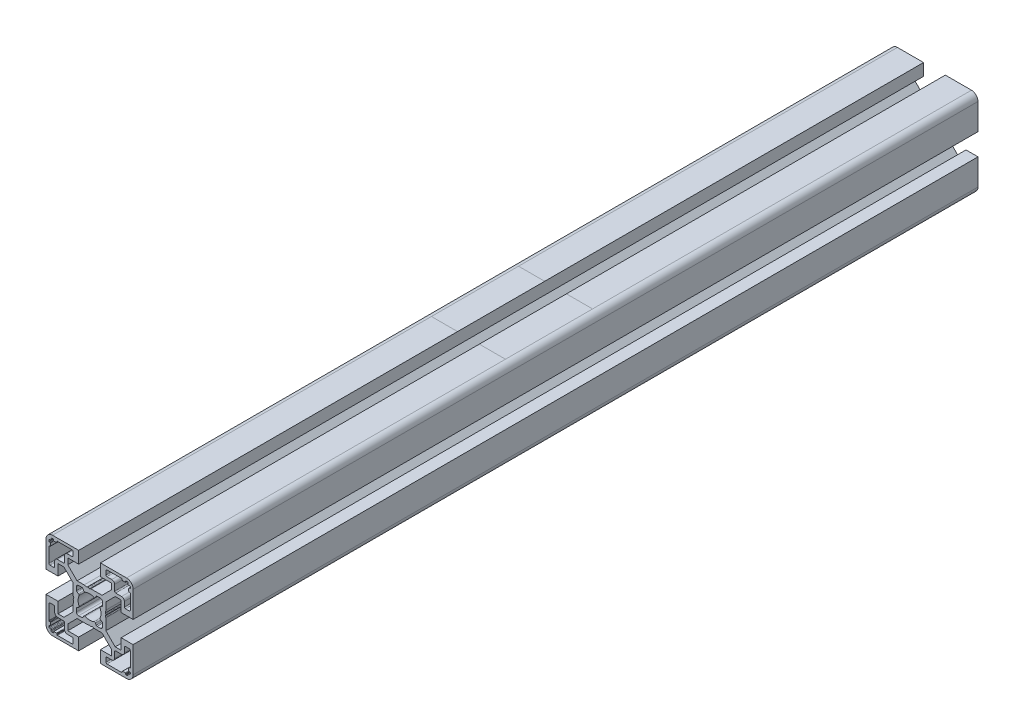
SolidWorks part; units mm, degrees
material "6063-T5"
ref_plane "Front Plane" through (0, 0, 0) normal (0, 0, 1) x (1, 0, 0)
ref_plane "Top Plane" through (0, 0, 0) normal (0, 1, 0) x (1, 0, 0)
ref_plane "Right Plane" through (0, 0, 0) normal (1, 0, 0) x (0, 0, -1)
ref_plane "Plan1" through (0, 0, 50) normal (0, 0, 1) x (1, 0, 0)
sketch "Esquisse1" plane through (0, 0, 50) normal (0, 0, 1) x (1, 0, 0)
  line L0 (-11.2645, -4.6769) -> (-11.2645, 2.1231)
  line L1 (-10.7645, 2.6231) -> (-9.0645, 2.6231)
  line L2 (-8.5645, 2.1231) -> (-8.5645, -0.0769)
  line L3 (-7.2645, -1.3769) -> (-4.5645, -1.3769)
  line L4 (-4.0645, -1.8769) -> (-4.0645, -4.5769)
  line L5 (-2.7645, -5.8769) -> (-0.5645, -5.8769)
  line L6 (-0.0645, -6.3769) -> (-0.0645, -8.0769)
  line L7 (-0.5645, -8.5769) -> (-7.3645, -8.5769)
  line L8 (-7.5645, -8.3769) -> (-7.5645, -8.0769)
  line L9 (-7.7645, -7.8769) -> (-8.9645, -7.8769)
  line L10 (-9.1645, -8.0769) -> (-9.1645, -8.3769)
  line L11 (-9.3645, -8.5769) -> (-9.8645, -8.5769)
  line L12 (-10.1645, -8.2769) -> (-10.1645, -7.7769)
  line L13 (-10.4645, -7.4769) -> (-10.9645, -7.4769)
  line L14 (-11.2645, -7.1769) -> (-11.2645, -6.6769)
  line L15 (-11.0645, -6.4769) -> (-10.7645, -6.4769)
  line L16 (-10.5645, -6.2769) -> (-10.5645, -5.0769)
  line L17 (-10.7645, -4.8769) -> (-11.0645, -4.8769)
  line L18 (14.9355, -8.0769) -> (14.9355, -6.3769)
  line L19 (15.4355, -5.8769) -> (17.6355, -5.8769)
  line L20 (18.9355, -4.5769) -> (18.9355, -1.8769)
  line L21 (19.4355, -1.3769) -> (22.1355, -1.3769)
  line L22 (23.4355, -0.0769) -> (23.4355, 2.1231)
  line L23 (23.9355, 2.6231) -> (25.6355, 2.6231)
  line L24 (26.1355, 2.1231) -> (26.1355, -4.6769)
  line L25 (25.9355, -4.8769) -> (25.6355, -4.8769)
  line L26 (25.4355, -5.0769) -> (25.4355, -6.2769)
  line L27 (25.6355, -6.4769) -> (25.9355, -6.4769)
  line L28 (26.1355, -6.6769) -> (26.1355, -7.1769)
  line L29 (25.8355, -7.4769) -> (25.3355, -7.4769)
  line L30 (25.0355, -7.7769) -> (25.0355, -8.2769)
  line L31 (24.7355, -8.5769) -> (24.2355, -8.5769)
  line L32 (24.0355, -8.3769) -> (24.0355, -8.0769)
  line L33 (23.8355, -7.8769) -> (22.6355, -7.8769)
  line L34 (22.4355, -8.0769) -> (22.4355, -8.3769)
  line L35 (22.2355, -8.5769) -> (15.4355, -8.5769)
  line L36 (-12.5645, 27.1231) -> (-12.5645, 15.1231)
  line L37 (-12.5645, 15.1231) -> (-7.0645, 15.1231)
  line L38 (-7.0645, 15.1231) -> (-7.0645, 20.1231)
  line L39 (-7.0645, 20.1231) -> (-4.3322, 20.1231)
  line L40 (-4.3322, 20.1231) -> (-0.0645, 15.8553)
  line L41 (-0.0645, 15.8553) -> (-0.0645, 10.7767)
  line L42 (0.0025, 10.5267) -> (0.2355, 10.1231)
  line L43 (0.2355, 10.1231) -> (0.0025, 9.7195)
  line L44 (0.0025, 9.2195) -> (0.1846, 8.9042)
  line L45 (0.1846, 8.9042) -> (-0.0645, 7.6231)
  line L46 (-0.0645, 7.6231) -> (-0.0645, 4.3908)
  line L47 (-0.0645, 4.3908) -> (-4.3322, 0.1231)
  line L48 (-4.3322, 0.1231) -> (-7.0645, 0.1231)
  line L49 (-7.0645, 0.1231) -> (-7.0645, 5.1231)
  line L50 (-7.0645, 5.1231) -> (-12.5645, 5.1231)
  line L51 (-12.5645, 5.1231) -> (-12.5645, -6.8769)
  line L52 (-9.5645, -9.8769) -> (2.4355, -9.8769)
  line L53 (2.4355, -9.8769) -> (2.4355, -4.3769)
  line L54 (2.4355, -4.3769) -> (-2.5645, -4.3769)
  line L55 (-2.5645, -4.3769) -> (-2.5645, -1.6447)
  line L56 (-2.5645, -1.6447) -> (1.7033, 2.6231)
  line L57 (1.7033, 2.6231) -> (6.7819, 2.6231)
  line L58 (7.0319, 2.6901) -> (7.4355, 2.9231)
  line L59 (7.4355, 2.9231) -> (7.8391, 2.6901)
  line L60 (8.3391, 2.6901) -> (8.6544, 2.8721)
  line L61 (8.6544, 2.8721) -> (9.9355, 2.6231)
  line L62 (9.9355, 2.6231) -> (13.1678, 2.6231)
  line L63 (13.1678, 2.6231) -> (17.4355, -1.6447)
  line L64 (17.4355, -1.6447) -> (17.4355, -4.3769)
  line L65 (17.4355, -4.3769) -> (12.4355, -4.3769)
  line L66 (12.4355, -4.3769) -> (12.4355, -9.8769)
  line L67 (12.4355, -9.8769) -> (24.4355, -9.8769)
  line L68 (27.4355, -6.8769) -> (27.4355, 5.1231)
  line L69 (27.4355, 5.1231) -> (21.9355, 5.1231)
  line L70 (21.9355, 5.1231) -> (21.9355, 0.1231)
  line L71 (21.9355, 0.1231) -> (19.2033, 0.1231)
  line L72 (19.2033, 0.1231) -> (14.9355, 4.3908)
  line L73 (14.9355, 4.3908) -> (14.9355, 9.4695)
  line L74 (14.8686, 9.7195) -> (14.6355, 10.1231)
  line L75 (14.6355, 10.1231) -> (14.8686, 10.5267)
  line L76 (14.8686, 11.0267) -> (14.6865, 11.342)
  line L77 (14.6865, 11.342) -> (14.9355, 12.6231)
  line L78 (14.9355, 12.6231) -> (14.9355, 15.8553)
  line L79 (14.9355, 15.8553) -> (19.2033, 20.1231)
  line L80 (19.2033, 20.1231) -> (21.9355, 20.1231)
  line L81 (21.9355, 20.1231) -> (21.9355, 15.1231)
  line L82 (21.9355, 15.1231) -> (27.4355, 15.1231)
  line L83 (27.4355, 15.1231) -> (27.4355, 27.1231)
  line L84 (24.4355, 30.1231) -> (12.4355, 30.1231)
  line L85 (12.4355, 30.1231) -> (12.4355, 24.6231)
  line L86 (12.4355, 24.6231) -> (17.4355, 24.6231)
  line L87 (17.4355, 24.6231) -> (17.4355, 21.8908)
  line L88 (17.4355, 21.8908) -> (13.1678, 17.6231)
  line L89 (13.1678, 17.6231) -> (8.0891, 17.6231)
  line L90 (7.8391, 17.5561) -> (7.4355, 17.3231)
  line L91 (7.4355, 17.3231) -> (7.0319, 17.5561)
  line L92 (6.5319, 17.5561) -> (6.2167, 17.3741)
  line L93 (6.2167, 17.3741) -> (4.9355, 17.6231)
  line L94 (4.9355, 17.6231) -> (1.7033, 17.6231)
  line L95 (1.7033, 17.6231) -> (-2.5645, 21.8908)
  line L96 (-2.5645, 21.8908) -> (-2.5645, 24.6231)
  line L97 (-2.5645, 24.6231) -> (2.4355, 24.6231)
  line L98 (2.4355, 24.6231) -> (2.4355, 30.1231)
  line L99 (2.4355, 30.1231) -> (-9.5645, 30.1231)
  line L100 (14.9355, 26.6231) -> (14.9355, 28.3231)
  line L101 (15.4355, 28.8231) -> (22.2355, 28.8231)
  line L102 (22.4355, 28.6231) -> (22.4355, 28.3231)
  line L103 (22.6355, 28.1231) -> (23.8355, 28.1231)
  line L104 (24.0355, 28.3231) -> (24.0355, 28.6231)
  line L105 (24.2355, 28.8231) -> (24.7355, 28.8231)
  line L106 (25.0355, 28.5231) -> (25.0355, 28.0231)
  line L107 (25.3355, 27.7231) -> (25.8355, 27.7231)
  line L108 (26.1355, 27.4231) -> (26.1355, 26.9231)
  line L109 (25.9355, 26.7231) -> (25.6355, 26.7231)
  line L110 (25.4355, 26.5231) -> (25.4355, 25.3231)
  line L111 (25.6355, 25.1231) -> (25.9355, 25.1231)
  line L112 (26.1355, 24.9231) -> (26.1355, 18.1231)
  line L113 (25.6355, 17.6231) -> (23.9355, 17.6231)
  line L114 (23.4355, 18.1231) -> (23.4355, 20.3231)
  line L115 (22.1355, 21.6231) -> (19.4355, 21.6231)
  line L116 (18.9355, 22.1231) -> (18.9355, 24.8231)
  line L117 (17.6355, 26.1231) -> (15.4355, 26.1231)
  line L118 (-11.2645, 18.1231) -> (-11.2645, 24.9231)
  line L119 (-11.0645, 25.1231) -> (-10.7645, 25.1231)
  line L120 (-10.5645, 25.3231) -> (-10.5645, 26.5231)
  line L121 (-10.7645, 26.7231) -> (-11.0645, 26.7231)
  line L122 (-11.2645, 26.9231) -> (-11.2645, 27.4231)
  line L123 (-10.9645, 27.7231) -> (-10.4645, 27.7231)
  line L124 (-10.1645, 28.0231) -> (-10.1645, 28.5231)
  line L125 (-9.8645, 28.8231) -> (-9.3645, 28.8231)
  line L126 (-9.1645, 28.6231) -> (-9.1645, 28.3231)
  line L127 (-8.9645, 28.1231) -> (-7.7645, 28.1231)
  line L128 (-7.5645, 28.3231) -> (-7.5645, 28.6231)
  line L129 (-7.3645, 28.8231) -> (-0.5645, 28.8231)
  line L130 (-0.0645, 28.3231) -> (-0.0645, 26.6231)
  line L131 (-0.5645, 26.1231) -> (-2.7645, 26.1231)
  line L132 (-4.0645, 24.8231) -> (-4.0645, 22.1231)
  line L133 (-4.5645, 21.6231) -> (-7.2645, 21.6231)
  line L134 (-8.5645, 20.3231) -> (-8.5645, 18.1231)
  line L135 (-9.0645, 17.6231) -> (-10.7645, 17.6231)
  line L136 (10.9262, 16.1231) -> (12.4355, 16.1231)
  line L137 (13.4355, 15.1231) -> (13.4355, 13.6138)
  line L138 (13.1703, 13.1723) -> (12.4933, 12.8123)
  line L139 (12.4933, 7.4338) -> (13.1703, 7.0739)
  line L140 (13.4355, 6.6324) -> (13.4355, 5.1231)
  line L141 (12.4355, 4.1231) -> (10.9262, 4.1231)
  line L142 (10.4848, 4.3883) -> (10.1248, 5.0654)
  line L143 (4.7463, 5.0654) -> (4.3863, 4.3883)
  line L144 (3.9449, 4.1231) -> (2.4355, 4.1231)
  line L145 (1.4355, 5.1231) -> (1.4355, 6.6324)
  line L146 (1.7008, 7.0739) -> (2.3778, 7.4338)
  line L147 (2.3778, 12.8123) -> (1.7008, 13.1723)
  line L148 (1.4355, 13.6138) -> (1.4355, 15.1231)
  line L149 (2.4355, 16.1231) -> (3.9449, 16.1231)
  line L150 (4.3863, 15.8578) -> (4.7463, 15.1808)
  line L151 (10.1248, 15.1808) -> (10.4848, 15.8578)
  arc A0 (-11.2645, 2.1231) -> (-10.7645, 2.6231) centre (-10.7645, 2.1231) cw
  arc A1 (-9.0645, 2.6231) -> (-8.5645, 2.1231) centre (-9.0645, 2.1231) cw
  arc A2 (-8.5645, -0.0769) -> (-7.2645, -1.3769) centre (-7.2645, -0.0769) ccw
  arc A3 (-4.5645, -1.3769) -> (-4.0645, -1.8769) centre (-4.5645, -1.8769) cw
  arc A4 (-4.0645, -4.5769) -> (-2.7645, -5.8769) centre (-2.7645, -4.5769) ccw
  arc A5 (-0.5645, -5.8769) -> (-0.0645, -6.3769) centre (-0.5645, -6.3769) cw
  arc A6 (-0.0645, -8.0769) -> (-0.5645, -8.5769) centre (-0.5645, -8.0769) cw
  arc A7 (-7.3645, -8.5769) -> (-7.5645, -8.3769) centre (-7.3645, -8.3769) cw
  arc A8 (-7.5645, -8.0769) -> (-7.7645, -7.8769) centre (-7.7645, -8.0769) ccw
  arc A9 (-8.9645, -7.8769) -> (-9.1645, -8.0769) centre (-8.9645, -8.0769) ccw
  arc A10 (-9.1645, -8.3769) -> (-9.3645, -8.5769) centre (-9.3645, -8.3769) cw
  arc A11 (-9.8645, -8.5769) -> (-10.1645, -8.2769) centre (-9.8645, -8.2769) cw
  arc A12 (-10.1645, -7.7769) -> (-10.4645, -7.4769) centre (-10.4645, -7.7769) ccw
  arc A13 (-10.9645, -7.4769) -> (-11.2645, -7.1769) centre (-10.9645, -7.1769) cw
  arc A14 (-11.2645, -6.6769) -> (-11.0645, -6.4769) centre (-11.0645, -6.6769) cw
  arc A15 (-10.7645, -6.4769) -> (-10.5645, -6.2769) centre (-10.7645, -6.2769) ccw
  arc A16 (-10.5645, -5.0769) -> (-10.7645, -4.8769) centre (-10.7645, -5.0769) ccw
  arc A17 (-11.0645, -4.8769) -> (-11.2645, -4.6769) centre (-11.0645, -4.6769) cw
  arc A18 (14.9355, -6.3769) -> (15.4355, -5.8769) centre (15.4355, -6.3769) cw
  arc A19 (17.6355, -5.8769) -> (18.9355, -4.5769) centre (17.6355, -4.5769) ccw
  arc A20 (18.9355, -1.8769) -> (19.4355, -1.3769) centre (19.4355, -1.8769) cw
  arc A21 (22.1355, -1.3769) -> (23.4355, -0.0769) centre (22.1355, -0.0769) ccw
  arc A22 (23.4355, 2.1231) -> (23.9355, 2.6231) centre (23.9355, 2.1231) cw
  arc A23 (25.6355, 2.6231) -> (26.1355, 2.1231) centre (25.6355, 2.1231) cw
  arc A24 (26.1355, -4.6769) -> (25.9355, -4.8769) centre (25.9355, -4.6769) cw
  arc A25 (25.6355, -4.8769) -> (25.4355, -5.0769) centre (25.6355, -5.0769) ccw
  arc A26 (25.4355, -6.2769) -> (25.6355, -6.4769) centre (25.6355, -6.2769) ccw
  arc A27 (25.9355, -6.4769) -> (26.1355, -6.6769) centre (25.9355, -6.6769) cw
  arc A28 (26.1355, -7.1769) -> (25.8355, -7.4769) centre (25.8355, -7.1769) cw
  arc A29 (25.3355, -7.4769) -> (25.0355, -7.7769) centre (25.3355, -7.7769) ccw
  arc A30 (25.0355, -8.2769) -> (24.7355, -8.5769) centre (24.7355, -8.2769) cw
  arc A31 (24.2355, -8.5769) -> (24.0355, -8.3769) centre (24.2355, -8.3769) cw
  arc A32 (24.0355, -8.0769) -> (23.8355, -7.8769) centre (23.8355, -8.0769) ccw
  arc A33 (22.6355, -7.8769) -> (22.4355, -8.0769) centre (22.6355, -8.0769) ccw
  arc A34 (22.4355, -8.3769) -> (22.2355, -8.5769) centre (22.2355, -8.3769) cw
  arc A35 (15.4355, -8.5769) -> (14.9355, -8.0769) centre (15.4355, -8.0769) cw
  arc A36 (-9.5645, 30.1231) -> (-12.5645, 27.1231) centre (-9.5645, 27.1231) ccw
  arc A37 (-0.0645, 10.7767) -> (0.0025, 10.5267) centre (0.4355, 10.7767) ccw
  arc A38 (0.0025, 9.7195) -> (0.0025, 9.2195) centre (0.4355, 9.4695) ccw
  arc A39 (-12.5645, -6.8769) -> (-9.5645, -9.8769) centre (-9.5645, -6.8769) ccw
  arc A40 (6.7819, 2.6231) -> (7.0319, 2.6901) centre (6.7819, 3.1231) ccw
  arc A41 (7.8391, 2.6901) -> (8.3391, 2.6901) centre (8.0891, 3.1231) ccw
  arc A42 (24.4355, -9.8769) -> (27.4355, -6.8769) centre (24.4355, -6.8769) ccw
  arc A43 (14.9355, 9.4695) -> (14.8686, 9.7195) centre (14.4355, 9.4695) ccw
  arc A44 (14.8686, 10.5267) -> (14.8686, 11.0267) centre (14.4355, 10.7767) ccw
  arc A45 (27.4355, 27.1231) -> (24.4355, 30.1231) centre (24.4355, 27.1231) ccw
  arc A46 (8.0891, 17.6231) -> (7.8391, 17.5561) centre (8.0891, 17.1231) ccw
  arc A47 (7.0319, 17.5561) -> (6.5319, 17.5561) centre (6.7819, 17.1231) ccw
  arc A48 (14.9355, 28.3231) -> (15.4355, 28.8231) centre (15.4355, 28.3231) cw
  arc A49 (22.2355, 28.8231) -> (22.4355, 28.6231) centre (22.2355, 28.6231) cw
  arc A50 (22.4355, 28.3231) -> (22.6355, 28.1231) centre (22.6355, 28.3231) ccw
  arc A51 (23.8355, 28.1231) -> (24.0355, 28.3231) centre (23.8355, 28.3231) ccw
  arc A52 (24.0355, 28.6231) -> (24.2355, 28.8231) centre (24.2355, 28.6231) cw
  arc A53 (24.7355, 28.8231) -> (25.0355, 28.5231) centre (24.7355, 28.5231) cw
  arc A54 (25.0355, 28.0231) -> (25.3355, 27.7231) centre (25.3355, 28.0231) ccw
  arc A55 (25.8355, 27.7231) -> (26.1355, 27.4231) centre (25.8355, 27.4231) cw
  arc A56 (26.1355, 26.9231) -> (25.9355, 26.7231) centre (25.9355, 26.9231) cw
  arc A57 (25.6355, 26.7231) -> (25.4355, 26.5231) centre (25.6355, 26.5231) ccw
  arc A58 (25.4355, 25.3231) -> (25.6355, 25.1231) centre (25.6355, 25.3231) ccw
  arc A59 (25.9355, 25.1231) -> (26.1355, 24.9231) centre (25.9355, 24.9231) cw
  arc A60 (26.1355, 18.1231) -> (25.6355, 17.6231) centre (25.6355, 18.1231) cw
  arc A61 (23.9355, 17.6231) -> (23.4355, 18.1231) centre (23.9355, 18.1231) cw
  arc A62 (23.4355, 20.3231) -> (22.1355, 21.6231) centre (22.1355, 20.3231) ccw
  arc A63 (19.4355, 21.6231) -> (18.9355, 22.1231) centre (19.4355, 22.1231) cw
  arc A64 (18.9355, 24.8231) -> (17.6355, 26.1231) centre (17.6355, 24.8231) ccw
  arc A65 (15.4355, 26.1231) -> (14.9355, 26.6231) centre (15.4355, 26.6231) cw
  arc A66 (-11.2645, 24.9231) -> (-11.0645, 25.1231) centre (-11.0645, 24.9231) cw
  arc A67 (-10.7645, 25.1231) -> (-10.5645, 25.3231) centre (-10.7645, 25.3231) ccw
  arc A68 (-10.5645, 26.5231) -> (-10.7645, 26.7231) centre (-10.7645, 26.5231) ccw
  arc A69 (-11.0645, 26.7231) -> (-11.2645, 26.9231) centre (-11.0645, 26.9231) cw
  arc A70 (-11.2645, 27.4231) -> (-10.9645, 27.7231) centre (-10.9645, 27.4231) cw
  arc A71 (-10.4645, 27.7231) -> (-10.1645, 28.0231) centre (-10.4645, 28.0231) ccw
  arc A72 (-10.1645, 28.5231) -> (-9.8645, 28.8231) centre (-9.8645, 28.5231) cw
  arc A73 (-9.3645, 28.8231) -> (-9.1645, 28.6231) centre (-9.3645, 28.6231) cw
  arc A74 (-9.1645, 28.3231) -> (-8.9645, 28.1231) centre (-8.9645, 28.3231) ccw
  arc A75 (-7.7645, 28.1231) -> (-7.5645, 28.3231) centre (-7.7645, 28.3231) ccw
  arc A76 (-7.5645, 28.6231) -> (-7.3645, 28.8231) centre (-7.3645, 28.6231) cw
  arc A77 (-0.5645, 28.8231) -> (-0.0645, 28.3231) centre (-0.5645, 28.3231) cw
  arc A78 (-0.0645, 26.6231) -> (-0.5645, 26.1231) centre (-0.5645, 26.6231) cw
  arc A79 (-2.7645, 26.1231) -> (-4.0645, 24.8231) centre (-2.7645, 24.8231) ccw
  arc A80 (-4.0645, 22.1231) -> (-4.5645, 21.6231) centre (-4.5645, 22.1231) cw
  arc A81 (-7.2645, 21.6231) -> (-8.5645, 20.3231) centre (-7.2645, 20.3231) ccw
  arc A82 (-8.5645, 18.1231) -> (-9.0645, 17.6231) centre (-9.0645, 18.1231) cw
  arc A83 (-10.7645, 17.6231) -> (-11.2645, 18.1231) centre (-10.7645, 18.1231) cw
  arc A84 (12.4355, 16.1231) -> (13.4355, 15.1231) centre (12.4355, 15.1231) cw
  arc A85 (13.4355, 13.6138) -> (13.1703, 13.1723) centre (12.9355, 13.6138) cw
  arc A86 (12.4933, 12.8123) -> (12.2678, 12.1754) centre (12.728, 12.3708) ccw
  arc A87 (12.2678, 12.1754) -> (12.2678, 8.0708) centre (7.4355, 10.1231) cw
  arc A88 (12.2678, 8.0708) -> (12.4933, 7.4338) centre (12.728, 7.8753) ccw
  arc A89 (13.1703, 7.0739) -> (13.4355, 6.6324) centre (12.9355, 6.6324) cw
  arc A90 (13.4355, 5.1231) -> (12.4355, 4.1231) centre (12.4355, 5.1231) cw
  arc A91 (10.9262, 4.1231) -> (10.4848, 4.3883) centre (10.9262, 4.6231) cw
  arc A92 (10.1248, 5.0654) -> (9.4878, 5.2908) centre (9.6833, 4.8306) ccw
  arc A93 (9.4878, 5.2908) -> (5.3832, 5.2908) centre (7.4355, 10.1231) cw
  arc A94 (5.3832, 5.2908) -> (4.7463, 5.0654) centre (5.1878, 4.8306) ccw
  arc A95 (4.3863, 4.3883) -> (3.9449, 4.1231) centre (3.9449, 4.6231) cw
  arc A96 (2.4355, 4.1231) -> (1.4355, 5.1231) centre (2.4355, 5.1231) cw
  arc A97 (1.4355, 6.6324) -> (1.7008, 7.0739) centre (1.9355, 6.6324) cw
  arc A98 (2.3778, 7.4338) -> (2.6033, 8.0708) centre (2.1431, 7.8753) ccw
  arc A99 (2.6033, 8.0708) -> (2.6033, 12.1754) centre (7.4355, 10.1231) cw
  arc A100 (2.6033, 12.1754) -> (2.3778, 12.8123) centre (2.1431, 12.3708) ccw
  arc A101 (1.7008, 13.1723) -> (1.4355, 13.6138) centre (1.9355, 13.6138) cw
  arc A102 (1.4355, 15.1231) -> (2.4355, 16.1231) centre (2.4355, 15.1231) cw
  arc A103 (3.9449, 16.1231) -> (4.3863, 15.8578) centre (3.9449, 15.6231) cw
  arc A104 (4.7463, 15.1808) -> (5.3832, 14.9553) centre (5.1878, 15.4155) ccw
  arc A105 (5.3832, 14.9553) -> (9.4878, 14.9553) centre (7.4355, 10.1231) cw
  arc A106 (9.4878, 14.9553) -> (10.1248, 15.1808) centre (9.6833, 15.4155) ccw
  arc A107 (10.4848, 15.8578) -> (10.9262, 16.1231) centre (10.9262, 15.6231) cw
extrude "Boss.-Extru.1" add sketch "Esquisse1" against normal blind 388
sketch "Esquisse2" plane through (0, 30.1231, 0) normal (0, 1, 0) x (1, 0, 0)
  line L0 (-12.5645, 338) -> (-12.5645, -50) construction
  line L1 (-12.5645, 164) -> (27.4355, 164)
  line L2 (-12.5645, 164) -> (-12.5645, 124)
  line L3 (-12.5645, 124) -> (27.4355, 124)
  line L4 (27.4355, 164) -> (27.4355, 124)
  line L5 (27.4355, 338) -> (27.4355, -50) construction
  line L6 (-12.5645, 144) -> (27.4355, 144) construction
  dimension "D1" = 40
split line "Ligne de séparation1"
